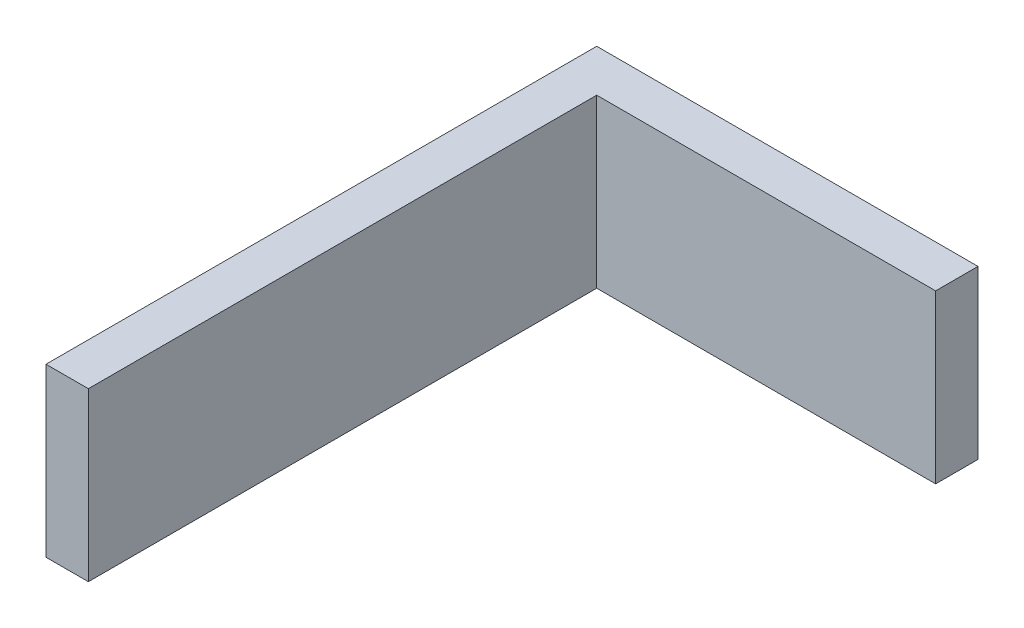
SolidWorks part; units mm, degrees
material "ABS"
ref_plane "Front Plane" through (0, 0, 0) normal (0, 0, 1) x (1, 0, 0)
ref_plane "Top Plane" through (0, 0, 0) normal (0, 1, 0) x (1, 0, 0)
ref_plane "Right Plane" through (0, 0, 0) normal (1, 0, 0) x (0, 0, -1)
sketch "Sketch1" plane through (0, 0, 0) normal (0, 1, 0) x (1, 0, 0)
  line L0 (0, 0) -> (85.725, 0)
  line L1 (85.725, 0) -> (85.725, -9.525)
  line L2 (85.725, -9.525) -> (9.525, -9.525)
  line L3 (9.525, -9.525) -> (9.525, -123.825)
  line L4 (9.525, -123.825) -> (0, -123.825)
  line L5 (0, -123.825) -> (0, 0)
  dimension "D1" = 9.525
  dimension "D2" = 9.525
  dimension "D3" = 114.3
  dimension "D4" = 76.2
extrude "Boss-Extrude1" add sketch "Sketch1" along normal blind 38.1
hole_wizard "CBORE for #4 Socket Head Cap Screw1" positions "Sketch3" profile "Sketch2" counterbore size "#4" standard "ANSI Inch"
sketch "Sketch3" plane through (0, 0, 0) normal (0, -1, 0) x (-1, 0, 0)
  line L0 (-4.7625, -123.825) -> (-4.7625, 0) construction
  line L1 (0, -123.825) -> (-9.525, -123.825) construction
  line L2 (-85.725, 0) -> (0, 0) construction
  line L4 (-85.725, -4.7625) -> (0, -4.7625) construction
  line L5 (-85.725, -9.525) -> (-85.725, 0) construction
  line L6 (0, 0) -> (0, -123.825) construction
  point P15 (-4.7625, -4.7625)
  point P17 (-4.7625, -39.6875)
  point P19 (-4.7625, -74.6125)
  point P23 (-39.6875, -4.7625)
  point P25 (-74.6125, -4.7625)
  point P27 (-4.7625, -109.5375)
  dimension "D1" = 34.925
  dimension "D2" = 34.925
  dimension "D3" = 34.925
  dimension "D4" = 34.925
  dimension "D5" = 34.925
sketch "Sketch2" plane through (4.7625, 0, 4.7625) normal (1, 0, 0) x (0, 0, -1)
  line L0 (0, 0) -> (0, 13.6806)
  line L1 (0, 13.6806) -> (1.6319, 12.7)
  line L2 (1.6319, 12.7) -> (1.6319, 4.7625)
  line L3 (1.6319, 4.7625) -> (1.9844, 4.7625)
  line L4 (1.9844, 4.7625) -> (1.9844, 0)
  line L5 (1.9844, 0) -> (0, 0)
  line L10 (0, 13.6806) -> (-1.632, 12.7) construction
  line L11 (0, -6.35) -> (0, 107.95) construction
  dimension "Hole Dia." = 3.2639
  dimension "Hole Depth" = 12.7
  dimension "C'Bore Dia." = 3.9688
  dimension "C'Bore Depth" = 4.7625
  dimension "Drill Angle" = 118
sketch "Sketch4" plane through (0, 0, 0) normal (-1, 0, 0) x (0, 0, 1)
  text T0 "Morpheus\r\n  Skates" font "BankGothic Lt BT" height in points 28
extrude "Cut-Extrude1" cut sketch "Sketch4" against normal blind 0.7937
chamfer "Chamfer1" distance 0.508 angle 45 6 edges at (42.8625, 0, 0) (85.725, 0, 4.7625) (47.625, 0, 9.525) (9.525, 0, 66.675) (4.7625, 0, 123.825) (0, 0, 61.9125)
